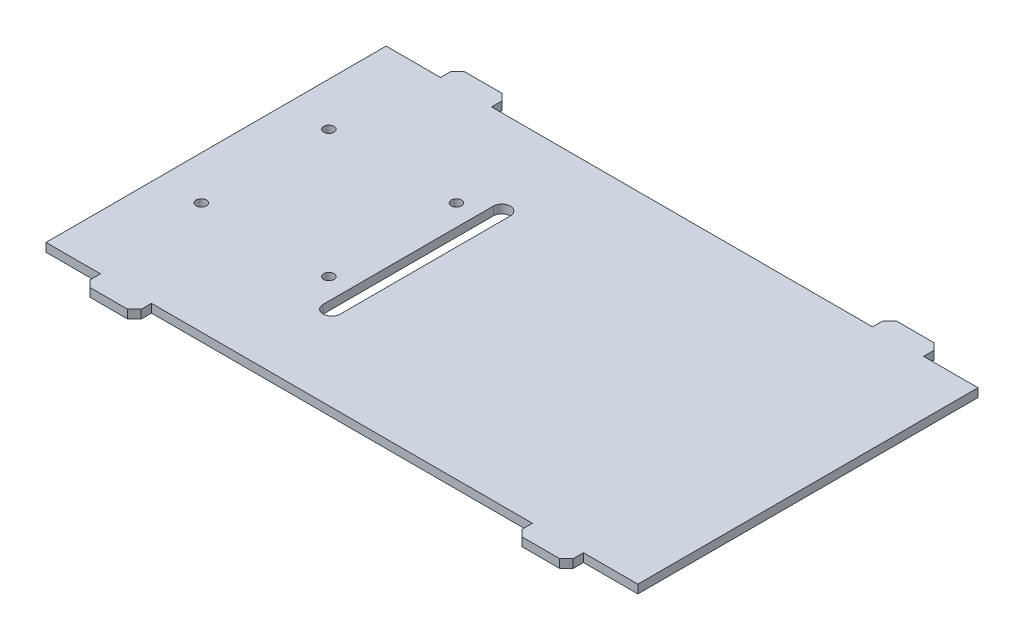
SolidWorks part; units mm, degrees
ref_plane "Front Plane" through (0, 0, 0) normal (0, 0, 1) x (1, 0, 0)
ref_plane "Top Plane" through (0, 0, 0) normal (0, 1, 0) x (1, 0, 0)
ref_plane "Right Plane" through (0, 0, 0) normal (1, 0, 0) x (0, 0, -1)
sketch "Sketch1" plane through (0, 0, 0) normal (0, 1, 0) x (1, 0, 0)
  line L0 (-87, -50) -> (-87, 50)
  line L1 (-87, 50) -> (87, 50)
  line L2 (87, 50) -> (87, -50)
  line L3 (87, -50) -> (-87, -50)
  line L4 (-28, 25) -> (-28, -25) construction
  line L5 (-25.5, 25) -> (-25.5, -25)
  line L6 (-30.5, 25) -> (-30.5, -25)
  arc A0 (-25.5, 25) -> (-30.5, 25) centre (-28, 25) ccw
  arc A1 (-30.5, -25) -> (-25.5, -25) centre (-28, -25) ccw
  arc A2 (-36.733, -15.6094) -> (-36.733, -18.6094) centre (-36.733, -17.1094) ccw construction
  arc A3 (-36.733, -15.6094) -> (-36.733, -18.6094) centre (-36.733, -17.1094) ccw
  arc A4 (-36.733, -18.6094) -> (-36.733, -15.6094) centre (-36.733, -17.1094) ccw construction
  arc A5 (-36.733, -18.6094) -> (-36.733, -15.6094) centre (-36.733, -17.1094) ccw
  arc A6 (-36.733, 18.8906) -> (-36.733, 21.8906) centre (-36.733, 20.3906) ccw construction
  arc A7 (-36.733, 21.8906) -> (-36.733, 18.8906) centre (-36.733, 20.3906) ccw construction
  arc A8 (-36.733, 18.8906) -> (-36.733, 21.8906) centre (-36.733, 20.3906) ccw
  arc A9 (-36.733, 21.8906) -> (-36.733, 18.8906) centre (-36.733, 20.3906) ccw
  arc A10 (-74.233, 21.8906) -> (-74.233, 18.8906) centre (-74.233, 20.3906) ccw construction
  arc A11 (-74.233, 18.8906) -> (-74.233, 21.8906) centre (-74.233, 20.3906) ccw construction
  arc A12 (-74.233, 21.8906) -> (-74.233, 18.8906) centre (-74.233, 20.3906) ccw
  arc A13 (-74.233, 18.8906) -> (-74.233, 21.8906) centre (-74.233, 20.3906) ccw
  arc A14 (-74.233, -15.6094) -> (-74.233, -18.6094) centre (-74.233, -17.1094) ccw construction
  arc A15 (-74.233, -18.6094) -> (-74.233, -15.6094) centre (-74.233, -17.1094) ccw construction
  arc A16 (-74.233, -15.6094) -> (-74.233, -18.6094) centre (-74.233, -17.1094) ccw
  arc A17 (-74.233, -18.6094) -> (-74.233, -15.6094) centre (-74.233, -17.1094) ccw
  point P3 (-87, 0)
  point P6 (0, 50)
  point P9 (-28, 0)
  dimension "D1" = 174
  dimension "D2" = 100
  dimension "D3" = 5
  dimension "D4" = 50
  dimension "D5" = 28
extrude "Boss-Extrude1" add sketch "Sketch1" along normal blind 2.5
sketch "Sketch2" plane through (0, 0, 50) normal (0, 0, 1) x (1, 0, 0)
  line L0 (-71, 1.25) -> (-56, 1.25) construction
  line L1 (-71, 2.5) -> (-56, 2.5)
  line L2 (-71, 0) -> (-56, 0)
  line L3 (-87, 2.5) -> (87, 2.5) construction
  line L4 (0, 0) -> (0, 14.7074) construction
  line L5 (71, 1.25) -> (56, 1.25) construction
  line L6 (71, 2.5) -> (56, 2.5)
  line L7 (71, 0) -> (56, 0)
  line L8 (-71, 0) -> (-71, 2.5)
  line L9 (-56, 0) -> (-56, 2.5)
  line L10 (56, 0) -> (56, 2.5)
  line L11 (71, 0) -> (71, 2.5)
  line L12 (-87, 0) -> (87, 0) construction
  arc A0 (-71, 2.5) -> (-71, 0) centre (-71, 1.25) ccw
  arc A1 (-56, 0) -> (-56, 2.5) centre (-56, 1.25) ccw
  arc A2 (71, 2.5) -> (71, 0) centre (71, 1.25) cw
  arc A3 (56, 0) -> (56, 2.5) centre (56, 1.25) cw
  point P2 (-63.5, 1.25)
  point P7 (-63.5, 2.5)
  point P18 (63.5, 1.25)
  point P31 (-63.5, 0)
  line M6 (-87, 0) -> (87, 0)
  line M8 (87, 2.5) -> (-87, 2.5)
  dimension "D1" = 15
  dimension "D2" = 16
extrude "Boss-Extrude2" add sketch "Sketch2" along normal blind 5 contours L9 L8 M6 M8 | L11 L10 M6 M8
mirror "Mirror1" about plane through (0, 0, 0) normal (0, 0, 1) of "Boss-Extrude2"
chamfer "Chamfer1" distance 2 angle 45 8 edges at (-56, 1.25, 55) (-71, 1.25, 55) (56, 1.25, 55) (71, 1.25, 55) (71, 1.25, -55) (56, 1.25, -55) (-56, 1.25, -55) (-71, 1.25, -55)
